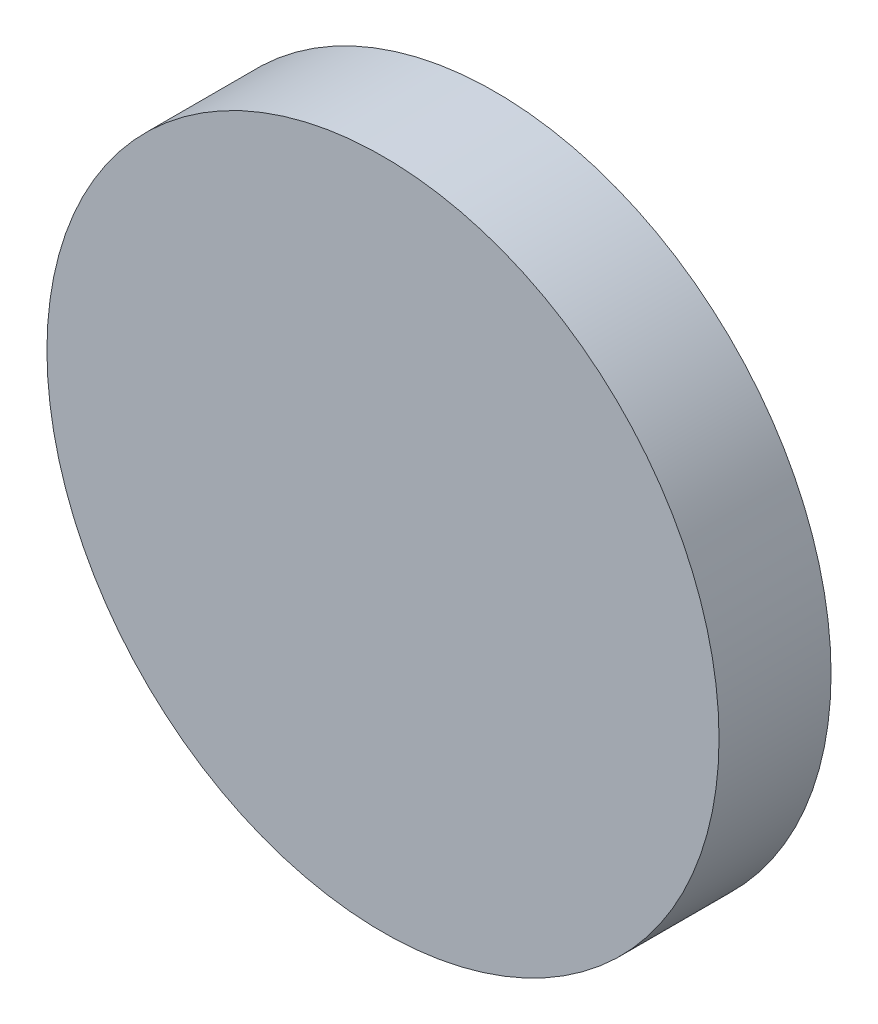
SolidWorks part; units mm, degrees
ref_plane "前视基准面" through (0, 0, 0) normal (0, 0, 1) x (1, 0, 0)
ref_plane "上视基准面" through (0, 0, 0) normal (0, 1, 0) x (1, 0, 0)
ref_plane "右视基准面" through (0, 0, 0) normal (1, 0, 0) x (0, 0, -1)
other "Configuration Table"
sketch "草图1" plane through (0, 0, 0) normal (0, 0, 1) x (1, 0, 0)
  circle A0 centre (0, 0) radius 21
  dimension "D1" = 42
extrude "凸台-拉伸1" add sketch "草图1" along normal blind 7
